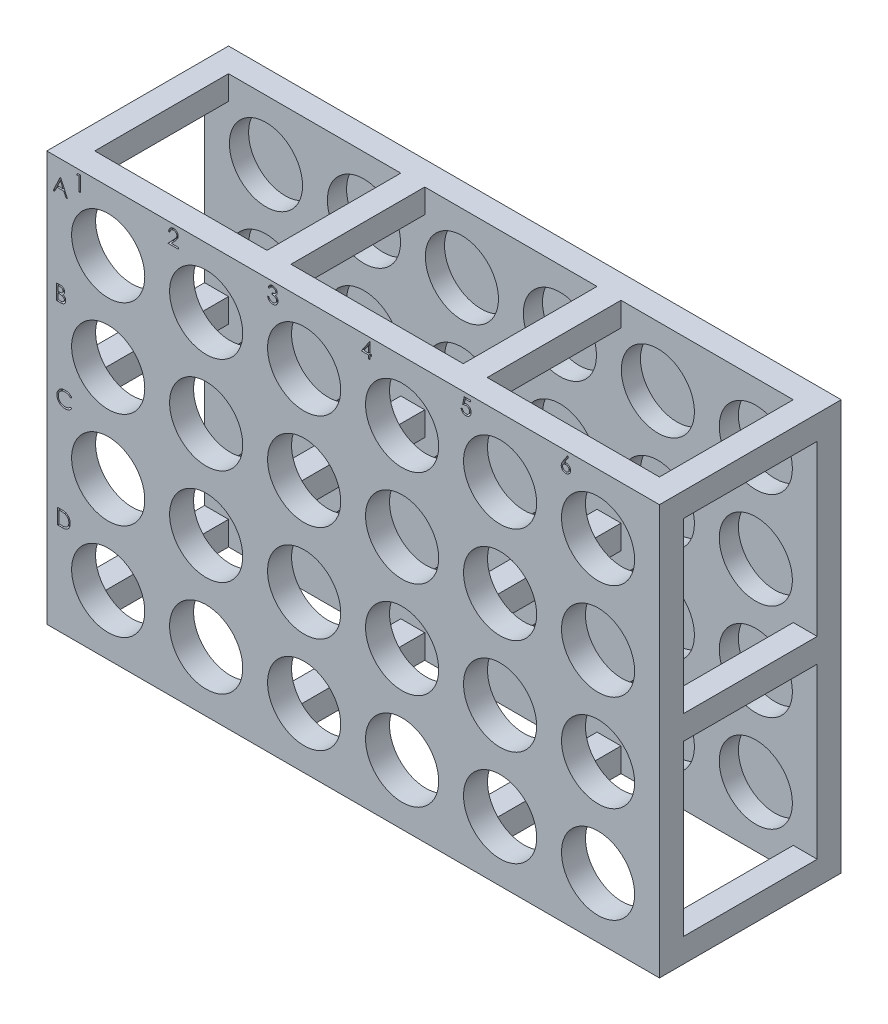
SolidWorks part; units mm, degrees
ref_plane "Front Plane" through (0, 0, 0) normal (0, 0, 1) x (1, 0, 0)
ref_plane "Top Plane" through (0, 0, 0) normal (0, 1, 0) x (1, 0, 0)
ref_plane "Right Plane" through (0, 0, 0) normal (1, 0, 0) x (0, 0, -1)
sketch "Sketch1" plane through (0, 0, 0) normal (0, 0, 1) x (1, 0, 0)
  line L1 (-54.6738, 25.2702) -> (73.0862, 25.2702)
  line L2 (-54.6738, 25.2702) -> (-54.6738, -60.2098)
  line L3 (-54.6738, -60.2098) -> (73.0862, -60.2098)
  line L4 (73.0862, 25.2702) -> (73.0862, -60.2098)
extrude "Boss-Extrude1" add sketch "Sketch1" along normal blind 5
sketch "Sketch2" plane through (0, 0, 5) normal (0, 0, 1) x (1, 0, 0)
  line L0 (-54.6738, 25.2702) -> (-54.6738, -60.2098) construction
  line L1 (73.0862, 25.2702) -> (-54.6738, 25.2702) construction
  circle A0 centre (-41.8688, 12.7492) radius 7.625
extrude "Cut-Extrude1" cut sketch "Sketch2" against normal through all
sketch "Sketch3" plane through (0, 0, 5) normal (0, 0, 1) x (1, 0, 0)
  line L1 (-54.6738, 25.2702) -> (-49.6738, 25.2702)
  line L2 (-54.6738, 25.2702) -> (-54.6738, 20.2702)
  line L3 (-54.6738, 20.2702) -> (-49.6738, 20.2702)
  line L4 (-49.6738, 25.2702) -> (-49.6738, 20.2702)
  dimension "D1" = 5
  dimension "D2" = 5
extrude "Boss-Extrude2" add sketch "Sketch3" along normal blind 13.95
pattern_linear "LPattern2" count 6 spacing 20.43 along (1, 0, 0) count 4 spacing 20.146 along (0, -1, 0) of "Cut-Extrude1"
sketch "Sketch4" plane through (0, 0, 5) normal (0, 0, 1) x (1, 0, 0)
  line L2 (-29.1538, 0.6242) -> (-34.1538, 0.6242)
  line L3 (-29.1538, 0.6242) -> (-29.1538, 5.6242)
  line L4 (-29.1538, 5.6242) -> (-34.1538, 5.6242)
  line L5 (-34.1538, 0.6242) -> (-34.1538, 5.6242)
  line L6 (-29.1538, 0.6242) -> (-34.1538, 5.6242) construction
  line L7 (-29.1538, 5.6242) -> (-34.1538, 0.6242) construction
  circle A0 centre (-41.8688, 12.7492) radius 7.625 construction
  circle A3 centre (-21.4388, 12.7492) radius 7.625 construction
  point P2 (-31.6538, 3.1242)
pattern_linear "LPattern5" count 4 spacing 40.92 along (1, 0, 0) count 3 spacing 40.24 along (0, -1, 0) of "Boss-Extrude2"
pattern_linear "LPattern6" count 2 spacing 122.76 along (0, 1, 0) count 2 spacing 80.48 along (1, 0, 0) of "Boss-Extrude2"
ref_plane "Plane1" through (0, 0, 18.95) normal (0, 0, -1) x (-1, 0, 0)
mirror "Mirror9" about plane through (0, 0, 18.95) normal (0, 0, -1) of bodies 114 111
sketch "Sketch5" plane through (0, 0, 37.9) normal (0, 0, 1) x (1, 0, 0)
  text T0 "A"
  text T1 "B\r\n"
  text T2 "C\r\n"
  text T3 "D\r\n"
  text T5 "1              2               3              4               5               6 "
  point P0 (-49.0416, 21.2429)
extrude "Cut-Extrude2" cut sketch "Sketch5" against normal blind 1
sketch "Sketch6" plane through (0, 0, 0) normal (0, 0, -1) x (-1, 0, 0)
  line L1 (54.6738, -60.2098) -> (-73.0862, -60.2098)
  line L2 (54.6738, -60.2098) -> (54.6738, 25.2702)
  line L3 (54.6738, 25.2702) -> (-73.0862, 25.2702)
  line L4 (-73.0862, -60.2098) -> (-73.0862, 25.2702)
extrude "Boss-Extrude3" add sketch "Sketch6" against normal blind 1
equation "\"platewidth\"=127.76"
equation "\"D1@Sketch1\"=\"platewidth\""
equation "\"plateheight\"=85.48"
equation "\"D2@Sketch1\"=\"plateheight\""
equation "\"od\"= \"od_meas\" + \"od_offset\""
equation "\"height\"= \"height_overall\" - \"neck_offset\""
equation "\"minspacing\"= 4'min padding between vials"
equation "\"nx\"= int ( ( \"platewidth\" - \"minspacing\" ) / ( \"od\" + \"minspacing\" ) )'force spacing on left and right ends"
equation "\"ny\"= int ( ( \"plateheight\" - \"minspacing\" ) / ( \"od\" + \"minspacing\" ) )"
equation "\"xspacing\"= ( \"platewidth\" - ( \"nx\" * \"od\" ) ) / ( \"nx\" + 1 )"
equation "\"yspacing\"= ( \"plateheight\" - ( \"ny\" * \"od\" ) ) / ( \"ny\" + 1 )"
equation "\"od_offset\"= 0.6'extra width to print vial holes"
equation "\"od_meas\" = 14.65'measured vial outer dimension (mm)"
equation "\"neck_offset\"= 9'distance from top of threads to wide point of vial"
equation "\"height_overall\" = 46.9'overall height of vial"
equation "\"D3@Sketch2\"=\"yspacing\" + (\"od\"/2)"
equation "\"D2@Sketch2\"= \"xspacing\" + \"od\"/2"
equation "\"D1@Boss-Extrude2\"= (\"height\"/2) - 5"
equation "\"D1@LPattern2\"= \"nx\""
equation "\"D3@LPattern2\"=\"od\" + \"xspacing\""
equation "\"D2@LPattern2\"= \"ny\""
equation "\"D4@LPattern2\"=\"od\" + \"yspacing\""
equation "\"D3@LPattern5\"=2*(\"platewidth\"-5)/(\"nx\")"
equation "\"D1@LPattern5\"=4"
equation "\"D4@LPattern5\"=2*(\"plateheight\"-5)/\"ny\""
equation "\"xpitch\"= \"od\" + \"xspacing\"'center to center distance of wells"
equation "\"D4@Sketch4\"= (\"minspacing\"+\"od\")/2"
equation "\"D3@Sketch4\"= \"xpitch\"/2"
equation "\"ypitch\"= \"od\" + \"yspacing\""
equation "\"D3@LPattern6\"=(\"platewidth\"-5)"
equation "\"D4@LPattern6\"=(\"plateheight\"-5)"
equation "\"D1@Sketch2\"=\"od\""
